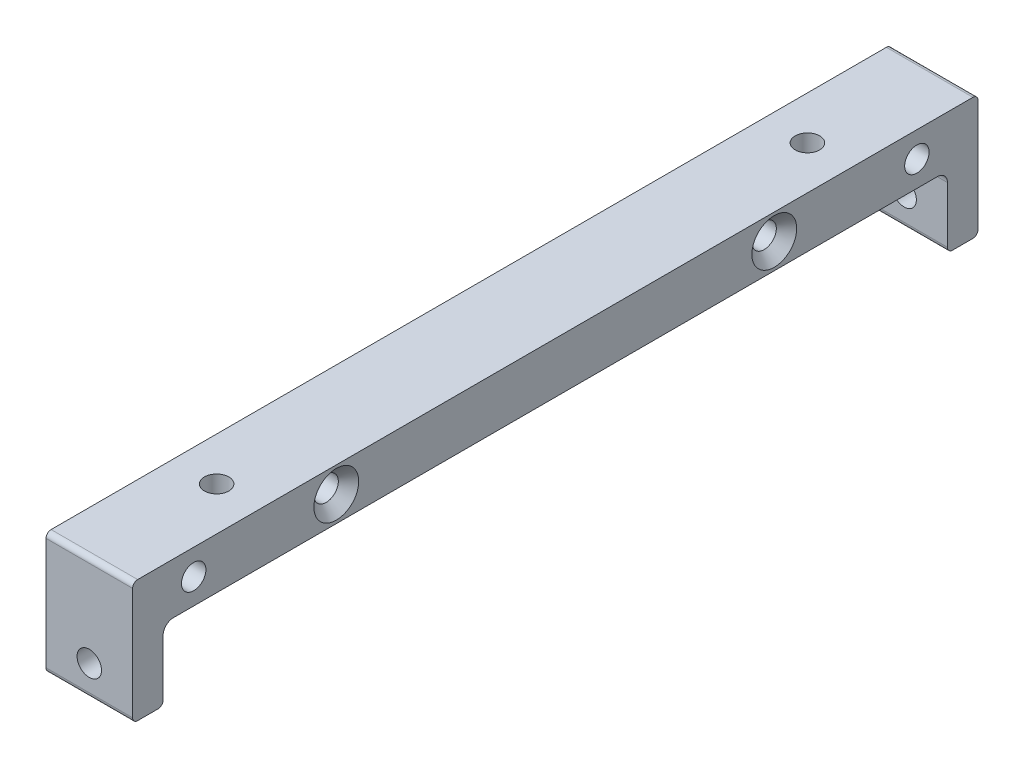
SolidWorks part; units mm, degrees
material "6061 Alloy"
ref_plane "Frontal" through (0, 0, 0) normal (0, 0, 1) x (1, 0, 0)
ref_plane "Superior" through (0, 0, 0) normal (0, 1, 0) x (1, 0, 0)
ref_plane "Direito" through (0, 0, 0) normal (1, 0, 0) x (0, 0, -1)
sketch "Sketch1" plane through (0, 0, 0) normal (0, 0, 1) x (1, 0, 0)
  line L1 (-4.25, -6) -> (4.25, -6)
  line L2 (-4.25, -6) -> (-4.25, 6)
  line L3 (-4.25, 6) -> (4.25, 6)
  line L4 (4.25, -6) -> (4.25, 6)
  line L5 (-4.25, -6) -> (4.25, 6) construction
  line L6 (-4.25, 6) -> (4.25, -6) construction
  point P0 (0, 0)
  dimension "D1" = 8.5
  dimension "D2" = 12
extrude "Boss-Extrude1" add sketch "Sketch1" along normal mid plane 83
sketch "Sketch2" plane through (4.25, 0, 0) normal (1, 0, 0) x (0, 0, -1)
  line L0 (-37.5, 1) -> (37.5, 1)
  line L1 (38.5, 0) -> (38.5, -6)
  line L2 (-41.5, -6) -> (41.5, -6) construction
  line L3 (38.5, -6) -> (-38.5, -6)
  line L4 (-38.5, -6) -> (-38.5, 0)
  line L5 (-41.5, 6) -> (41.5, 6) construction
  line L6 (-41.5, -6) -> (-41.5, 6) construction
  line L7 (41.5, -6) -> (41.5, 6) construction
  arc A0 (-37.5, 1) -> (-38.5, 0) centre (-37.5, 0) ccw
  arc A1 (37.5, 1) -> (38.5, 0) centre (37.5, 0) cw
  dimension "D4" = 1
  dimension "D5" = 1
  dimension "D1" = 5
  dimension "D2" = 3
  dimension "D3" = 3
extrude "Cut-Extrude1" cut sketch "Sketch2" against normal through all
fillet "Fillet1" radius 0.5 6 edges at (0, 6, -41.5) (0, 6, 41.5) (0, -6, -41.5) (0, -6, -38.5) (0, -6, 38.5) (0, -6, 41.5)
hole_wizard "M2 Hole1 - J" positions "Sketch10" profile "Sketch9" hole size "M2" standard "DIN"
sketch "Sketch10" plane through (4.25, 0, 0) normal (1, 0, 0) x (0, 0, -1)
  line L0 (-41, 6) -> (41, 6) construction
  line L1 (-41.5, -5.5) -> (-41.5, 5.5) construction
  line L2 (41.5, -5.5) -> (41.5, 5.5) construction
  point P0 (-35.5, 3.5)
  point P2 (35.5, 3.5)
  dimension "D1" = 2.5
  dimension "D2" = 6
  dimension "D3" = 6
sketch "Sketch9" plane through (4.25, 3.5, 35.5) normal (0, 1, 0) x (0, 0, -1)
  line L0 (0, 0) -> (0, 5.721)
  line L1 (0, 5.721) -> (1.2, 5)
  line L2 (1.2, 5) -> (1.2, 0)
  line L5 (1.2, 0) -> (0, 0)
  line L10 (0, 5.721) -> (-1.2, 5) construction
  line L11 (0, -6.35) -> (0, 107.95) construction
  dimension "Hole Dia." = 2.4
  dimension "Hole Depth" = 5
  dimension "Drill Angle" = 118
hole_wizard "M2 Hole2 - K" positions "Sketch4" profile "Sketch3" countersink size "M2" standard "DIN" end condition through all
sketch "Sketch4" plane through (4.25, 0, 0) normal (1, 0, 0) x (0, 0, -1)
  line L0 (-41, 6) -> (41, 6) construction
  line L1 (-41.5, -5.5) -> (-41.5, 5.5) construction
  line L2 (41.5, -5.5) -> (41.5, 5.5) construction
  point P0 (-21.5, 3.5)
  point P2 (21.5, 3.5)
  dimension "D1" = 2.5
  dimension "D2" = 20
  dimension "D3" = 20
sketch "Sketch3" plane through (4.25, 3.5, 21.5) normal (0, 1, 0) x (0, 0, -1)
  line L0 (0, 0) -> (0, 8.5)
  line L1 (0, 8.5) -> (1.2, 8.5)
  line L2 (1.2, 8.5) -> (1.2, 1)
  line L3 (1.2, 1) -> (2.2, 0)
  line L5 (2.2, 0) -> (0, 0)
  line L6 (-1.2, 1) -> (-2.2, 0) construction
  line L11 (0, -6.35) -> (0, 107.95) construction
  dimension "Thru Hole Dia." = 2.4
  dimension "Thru Hole Depth" = 8.5
  dimension "Near C'Sink Dia." = 4.4
  dimension "Near C'Sink Angle" = 90
hole_wizard "M2 Hole3 - L" positions "Sketch8" profile "Sketch7" hole size "M2" standard "DIN"
sketch "Sketch8" plane through (0, 0, 41.5) normal (0, 0, 1) x (1, 0, 0)
  line L0 (4.25, -6) -> (-4.25, -6) construction
  point P0 (0, -3)
  dimension "D1" = 3
sketch "Sketch7" plane through (0, -3, 41.5) normal (1, 0, 0) x (0, -1, 0)
  line L0 (0, 0) -> (0, 10.721)
  line L1 (0, 10.721) -> (1.2, 10)
  line L2 (1.2, 10) -> (1.2, 0)
  line L5 (1.2, 0) -> (0, 0)
  line L10 (0, 10.721) -> (-1.2, 10) construction
  line L11 (0, -6.35) -> (0, 107.95) construction
  dimension "Hole Dia." = 2.4
  dimension "Hole Depth" = 10
  dimension "Drill Angle" = 118
hole_wizard "M2 Hole4 - M" positions "Sketch15" profile "Sketch14" hole size "M2" standard "DIN" end condition through all
sketch "Sketch15" plane through (0, 6, 0) normal (0, 1, 0) x (1, 0, 0)
  line L0 (-4.25, -41) -> (-4.25, 41) construction
  line L1 (-4.25, 41.5) -> (4.25, 41.5) construction
  line L2 (4.25, -41.5) -> (-4.25, -41.5) construction
  point P0 (0, 29)
  point P2 (0, -29)
  dimension "D1" = 4.25
  dimension "D2" = 12.5
  dimension "D3" = 12.5
sketch "Sketch14" plane through (0, 6, -29) normal (1, 0, 0) x (0, 0, 1)
  line L0 (0, 0) -> (0, 12)
  line L1 (0, 12) -> (1.2, 12)
  line L2 (1.2, 12) -> (1.2, 0)
  line L5 (1.2, 0) -> (0, 0)
  line L11 (0, -6.35) -> (0, 107.95) construction
  dimension "Thru Hole Dia." = 2.4
  dimension "Thru Hole Depth" = 12
hole_wizard "M2 Hole5 - N" positions "Sketch12" profile "Sketch11" hole size "M2" standard "DIN"
sketch "Sketch12" plane through (-4.25, 0, 0) normal (-1, 0, 0) x (0, 0, 1)
  line L0 (41, 6) -> (-41, 6) construction
  point P0 (0, 3.5)
  dimension "D1" = 2.5
sketch "Sketch11" plane through (-4.25, 3.5, 0) normal (0, 1, 0) x (0, 0, 1)
  line L0 (0, 0) -> (0, 4.721)
  line L1 (0, 4.721) -> (1.2, 4)
  line L2 (1.2, 4) -> (1.2, 0)
  line L5 (1.2, 0) -> (0, 0)
  line L10 (0, 4.721) -> (-1.2, 4) construction
  line L11 (0, -6.35) -> (0, 107.95) construction
  dimension "Hole Dia." = 2.4
  dimension "Hole Depth" = 4
  dimension "Drill Angle" = 118
hole_wizard "M2 Hole6 - P" positions "Sketch17" profile "Sketch16" hole size "M2" standard "DIN"
sketch "Sketch17" plane through (0, 0, -41.5) normal (0, 0, -1) x (-1, 0, 0)
  line L0 (4.25, 5.5) -> (4.25, -5.5) construction
  line L1 (-4.25, 6) -> (4.25, 6) construction
  point P0 (0, -3)
  dimension "D1" = 4.25
  dimension "D2" = 9
sketch "Sketch16" plane through (0, -3, -41.5) normal (1, 0, 0) x (0, 1, 0)
  line L0 (0, 0) -> (0, 10.721)
  line L1 (0, 10.721) -> (1.2, 10)
  line L2 (1.2, 10) -> (1.2, 0)
  line L5 (1.2, 0) -> (0, 0)
  line L10 (0, 10.721) -> (-1.2, 10) construction
  line L11 (0, -6.35) -> (0, 107.95) construction
  dimension "Hole Dia." = 2.4
  dimension "Hole Depth" = 10
  dimension "Drill Angle" = 118
